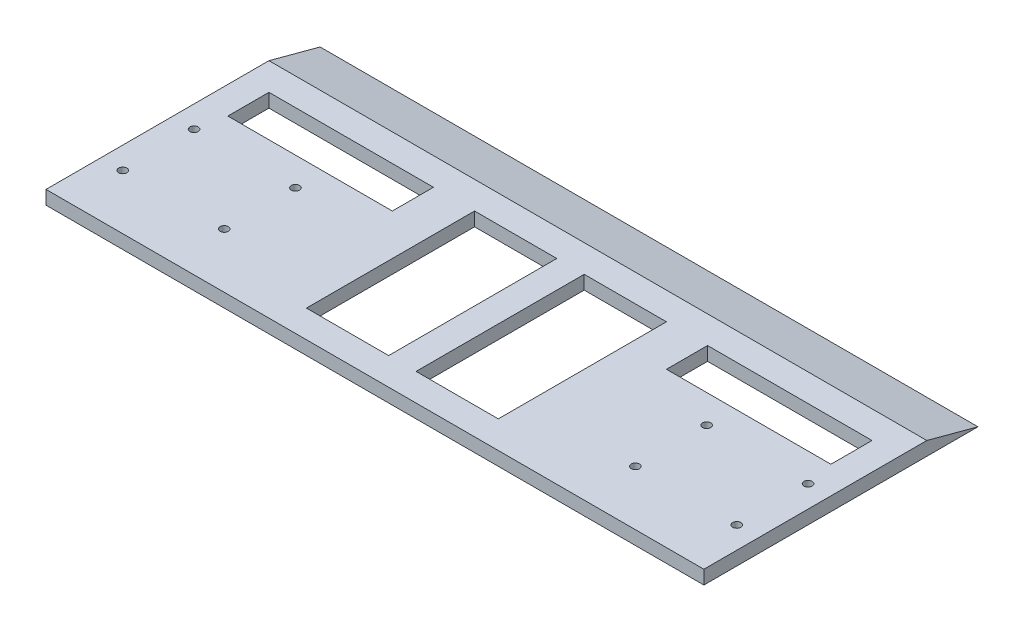
SolidWorks part; units mm, degrees
ref_plane "前视基准面" through (0, 0, 0) normal (0, 0, 1) x (1, 0, 0)
ref_plane "上视基准面" through (0, 0, 0) normal (0, 1, 0) x (1, 0, 0)
ref_plane "右视基准面" through (0, 0, 0) normal (1, 0, 0) x (0, 0, -1)
sketch "草图1" plane through (0, 0, 0) normal (0, 1, 0) x (1, 0, 0)
  line L1 (0, 0) -> (240, 0)
  line L2 (0, 0) -> (0, -100)
  line L3 (0, -100) -> (240, -100)
  line L4 (240, 0) -> (240, -100)
  dimension "D1" = 240
  dimension "D2" = 100
extrude "凸台-拉伸1" add sketch "草图1" along normal mid plane 5
sketch "草图2" plane through (240, 0, 0) normal (1, 0, 0) x (0, 0, -1)
  line L0 (0, -2.5) -> (-18.6603, 2.5)
  line L1 (-100, 2.5) -> (0, 2.5) construction
  line L2 (-100, -2.5) -> (0, -2.5) construction
  line L3 (0, 2.5) -> (0, -2.5) construction
  line L4 (0, 2.5) -> (0, -2.5)
  line L5 (-18.6603, 2.5) -> (0, 2.5)
  dimension "D1" = 15
extrude "切除-拉伸1" cut sketch "草图2" against normal through all
sketch "草图3" plane through (0, 2.5, 0) normal (0, 1, 0) x (1, 0, 0)
  line L0 (120, 0) -> (120, -100) construction
  line L1 (240, 0) -> (0, 0) construction
  line L2 (0, -100) -> (240, -100) construction
  line L4 (26.5, -56.683) -> (26.5, -89.3228) construction
  line L5 (16.6982, -67) -> (61.1867, -67) construction
  line L6 (213.5, -56.683) -> (213.5, -89.3228) construction
  circle A0 centre (45, -80) radius 1.5
  circle A2 centre (45, -54) radius 1.5
  circle A3 centre (8, -80) radius 1.5
  circle A4 centre (8, -54) radius 1.5
  circle A5 centre (195, -80) radius 1.5
  circle A6 centre (195, -54) radius 1.5
  circle A7 centre (232, -80) radius 1.5
  circle A8 centre (232, -54) radius 1.5
  dimension "D1" = 3
  dimension "D3" = 20
  dimension "D4" = 26
  dimension "D5" = 37
  dimension "D2" = 187
extrude "切除-拉伸2" cut sketch "草图3" against normal through all
sketch "草图4" plane through (0, 2.5, 0) normal (0, 1, 0) x (1, 0, 0)
  circle A0 centre (195, -54) radius 1.5
  circle A1 centre (232, -80) radius 1.5
  circle A2 centre (232, -54) radius 1.5
  circle A3 centre (45, -54) radius 1.5
  circle A4 centre (8, -54) radius 1.5
  circle A5 centre (8, -80) radius 1.5
  circle A6 centre (45, -80) radius 1.5
  dimension "D1" = 3
sketch "草图5" plane through (0, 2.5, 0) normal (0, 1, 0) x (1, 0, 0)
  line L0 (0, -18.6603) -> (240, -18.6603) construction
  line L1 (85, -28.6603) -> (155, -28.6603)
  line L2 (85, -28.6603) -> (85, -90)
  line L3 (85, -90) -> (155, -90)
  line L4 (155, -28.6603) -> (155, -90)
  line L5 (0, -100) -> (240, -100) construction
  line L6 (0, -18.6603) -> (0, -100) construction
  line L7 (240, -100) -> (240, -18.6603) construction
  dimension "D1" = 10
  dimension "D2" = 10
  dimension "D3" = 85
  dimension "D4" = 85
extrude "切除-拉伸4" cut sketch "草图5" against normal blind 10
sketch "草图6" plane through (0, 2.5, 0) normal (0, 1, 0) x (1, 0, 0)
  line L0 (0, -18.6603) -> (0, -100) construction
  line L1 (70, -28.6603) -> (10, -28.6603)
  line L2 (70, -28.6603) -> (70, -43.6603)
  line L3 (70, -43.6603) -> (10, -43.6603)
  line L4 (10, -28.6603) -> (10, -43.6603)
  line L5 (170, -28.6603) -> (230, -28.6603)
  line L6 (170, -28.6603) -> (170, -43.6603)
  line L7 (170, -43.6603) -> (230, -43.6603)
  line L8 (230, -28.6603) -> (230, -43.6603)
  line L9 (240, -100) -> (240, -18.6603) construction
  line L10 (0, -18.6603) -> (240, -18.6603) construction
  dimension "D1" = 10
  dimension "D2" = 10
  dimension "D3" = 10
extrude "切除-拉伸5" cut sketch "草图6" against normal blind 10
sketch "草图7" plane through (0, 0, 28.6603) normal (0, 0, 1) x (1, 0, 0)
  line L0 (155, 2.5) -> (85, 2.5) construction
  line L1 (115, 2.5) -> (125, 2.5)
  line L2 (115, 2.5) -> (115, -2.5)
  line L3 (115, -2.5) -> (125, -2.5)
  line L4 (125, 2.5) -> (125, -2.5)
  line L5 (155, -2.5) -> (85, -2.5) construction
  line L6 (155, -2.5) -> (155, 2.5) construction
  line L7 (85, -2.5) -> (85, 2.5) construction
  point P8 (125, 0)
  dimension "D1" = 30
  dimension "D2" = 30
extrude "凸台-拉伸2" add sketch "草图7" along normal blind 70
chamfer "倒角1" distance 1.12 angle 45 8 edges at (232, -2.5, 81.5) (232, -2.5, 52.5) (195, -2.5, 55.5) (195, -2.5, 78.5) (45, -2.5, 81.5) (8, -2.5, 78.5) (8, -2.5, 55.5) (45, -2.5, 52.5)
